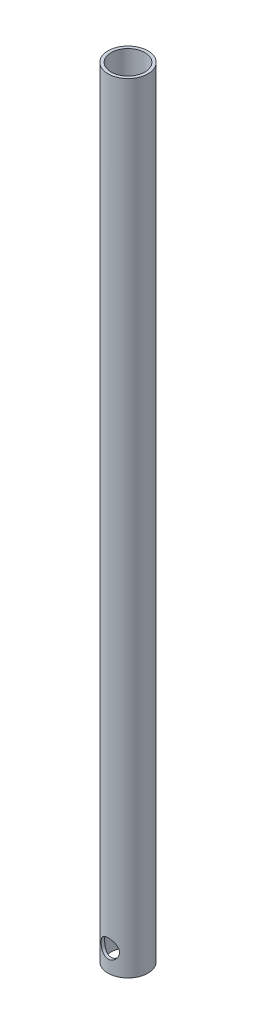
SolidWorks part; units mm, degrees
ref_plane "前视基准面" through (0, 0, 0) normal (0, 0, 1) x (1, 0, 0)
ref_plane "上视基准面" through (0, 0, 0) normal (0, 1, 0) x (1, 0, 0)
ref_plane "右视基准面" through (0, 0, 0) normal (1, 0, 0) x (0, 0, -1)
other "Configuration Table"
sketch "草图1" plane through (0, 0, 0) normal (0, 1, 0) x (1, 0, 0)
  circle A0 centre (0, 0) radius 6.5
  circle A1 centre (0, 0) radius 5.5
  dimension "D1" = 1
extrude "凸台-拉伸1" add sketch "草图1" along normal blind 253.8
sketch "草图2" plane through (0, 0, 0) normal (0, 0, 1) x (1, 0, 0)
  line L0 (0, 0) -> (0, 7) construction
  circle A0 centre (0, 7) radius 3
extrude "切除-拉伸1" cut sketch "草图2" against normal through all and the other way through all
